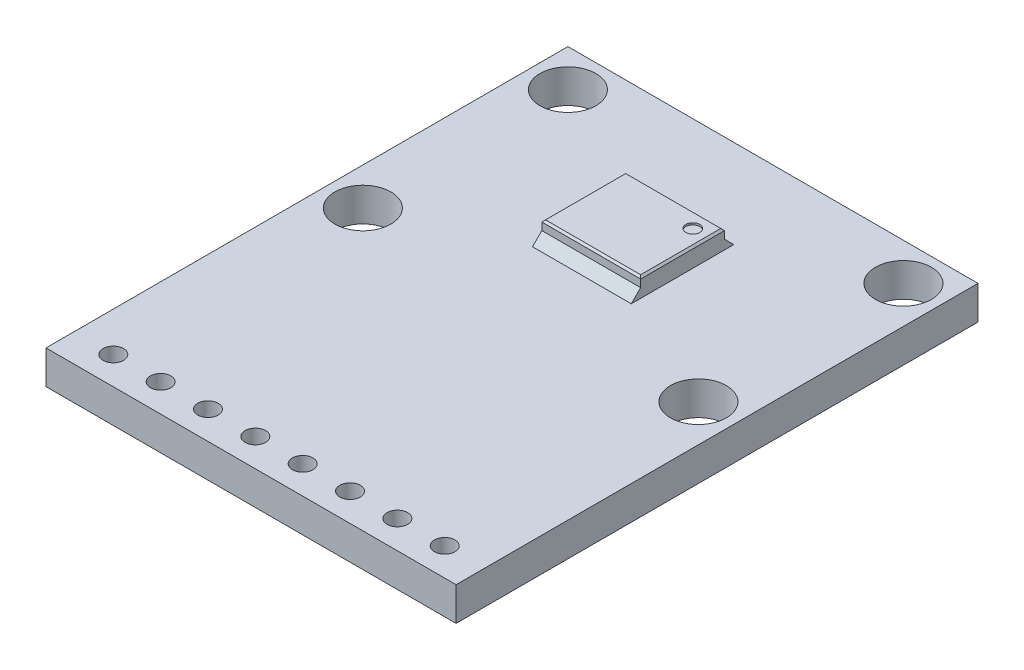
SolidWorks part; units mm, degrees
ref_plane "Front Plane" through (0, 0, 0) normal (0, 0, 1) x (1, 0, 0)
ref_plane "Top Plane" through (0, 0, 0) normal (0, 1, 0) x (1, 0, 0)
ref_plane "Right Plane" through (0, 0, 0) normal (1, 0, 0) x (0, 0, -1)
sketch "Sketch1" plane through (0, 0, 0) normal (0, 1, 0) x (1, 0, 0)
  line L1 (-11, 14) -> (11, 14)
  line L2 (-11, 14) -> (-11, -14)
  line L3 (-11, -14) -> (11, -14)
  line L4 (11, 14) -> (11, -14)
  line L5 (-11, 14) -> (11, -14) construction
  line L6 (-11, -14) -> (11, 14) construction
  circle A0 centre (-9, 12) radius 1.5
  circle A1 centre (9, 12) radius 1.5
  circle A2 centre (9, 1) radius 1.5
  circle A3 centre (-9, 1) radius 1.5
  circle A4 centre (-8.89, -12.5) radius 0.55
  circle A5 centre (-6.35, -12.5) radius 0.55
  circle A6 centre (-3.81, -12.5) radius 0.55
  circle A7 centre (-1.27, -12.5) radius 0.55
  circle A8 centre (1.27, -12.5) radius 0.55
  circle A9 centre (3.81, -12.5) radius 0.55
  circle A10 centre (6.35, -12.5) radius 0.55
  circle A11 centre (8.89, -12.5) radius 0.55
  point P0 (0, 0)
  point P19 (0, 14)
  dimension "D3" = 3
  dimension "D9" = 1.1
  dimension "D1" = 22
  dimension "D2" = 28
  dimension "D4" = 11
  dimension "D5" = 18
  dimension "D6" = 9
  dimension "D7" = 2
  dimension "D10" = 2.11
  dimension "D11" = 1.5
  dimension "D8" = 8
extrude "Boss-Extrude1" add sketch "Sketch1" along normal blind 1.8
sketch "Sketch2" plane through (0, 1.8, 0) normal (0, 1, 0) x (1, 0, 0)
  line L1 (-2.65, 8.75) -> (2.65, 8.75)
  line L2 (-2.65, 8.75) -> (-2.65, 4.25)
  line L3 (-2.65, 4.25) -> (2.65, 4.25)
  line L4 (2.65, 8.75) -> (2.65, 4.25)
  line L5 (-2.65, 8.75) -> (2.65, 4.25) construction
  line L6 (-2.65, 4.25) -> (2.65, 8.75) construction
  circle A0 centre (9, 12) radius 1.5 construction
  point P0 (0, 6.5)
  point P5 (0, 7.1552)
  dimension "D1" = 5.3
  dimension "D2" = 4.5
  dimension "D3" = 5.5
extrude "Boss-Extrude2" add sketch "Sketch2" along normal blind 1
chamfer "Chamfer1" distance 0.5 angle 45 2 edges at (0, 1.8, -8.75) (0, 1.8, -4.25)
chamfer "Chamfer2" distance 0.1 angle 45 4 edges at (0, 2.8, -4.25) (-2.65, 2.8, -6.5) (0, 2.8, -8.75) (2.65, 2.8, -6.5)
sketch "Sketch3" plane through (0, 2.8, 0) normal (0, 1, 0) x (1, 0, 0)
  line L0 (2.55, 4.35) -> (2.55, 8.65) construction
  line L1 (2.55, 8.65) -> (-2.55, 8.65) construction
  circle A0 centre (1.8, 7.9) radius 0.375
  point P4 (0, 0)
  point P6 (0, 0)
  dimension "D3" = 0.75
  dimension "D1" = 0.75
  dimension "D2" = 0.75
extrude "Cut-Extrude1" cut sketch "Sketch3" against normal blind 0.1
equation "\"D6@Sketch1\"=\"D5@Sketch1\"/2"
equation "\"D10@Sketch1\"=(22-17.78)/2"
